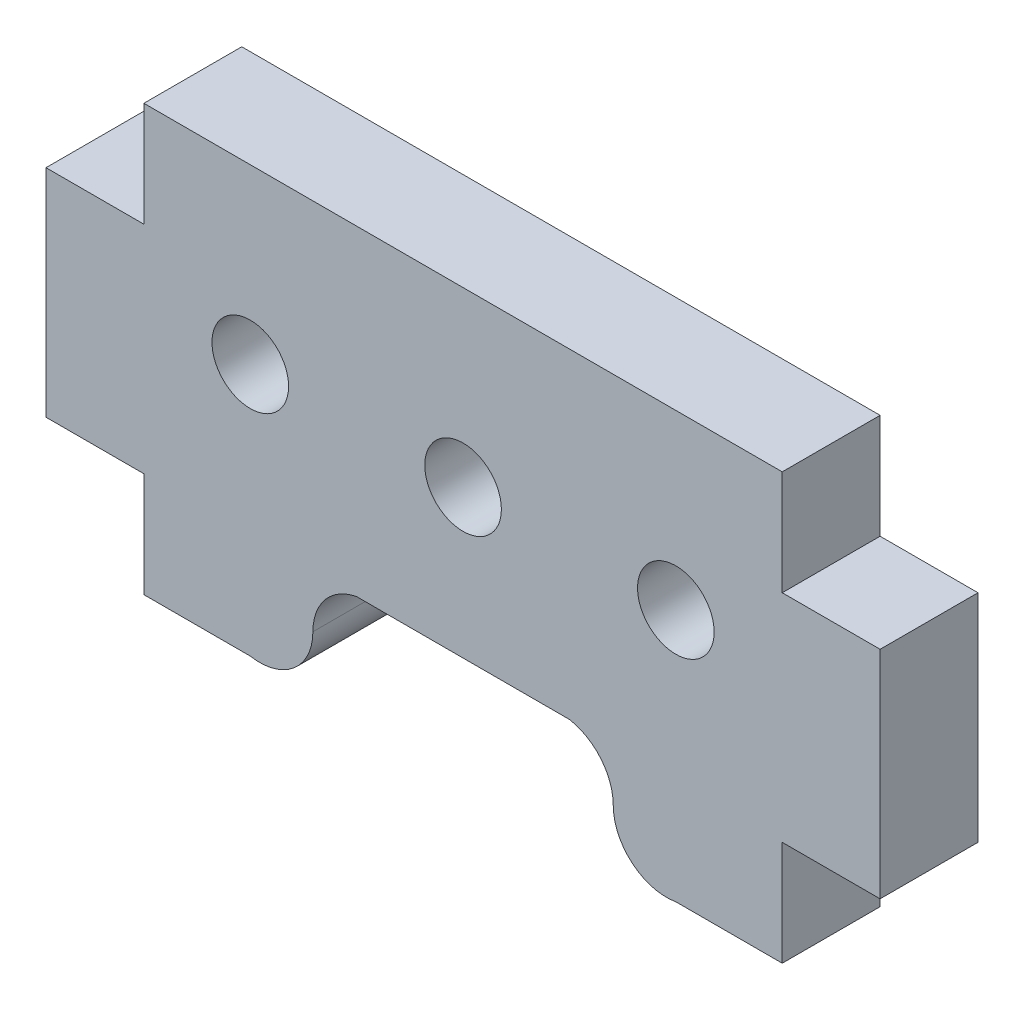
SolidWorks part; units mm, degrees
ref_plane "Front Plane" through (0, 0, 0) normal (0, 0, 1) x (1, 0, 0)
ref_plane "Top Plane" through (0, 0, 0) normal (0, 1, 0) x (1, 0, 0)
ref_plane "Right Plane" through (0, 0, 0) normal (1, 0, 0) x (0, 0, -1)
sketch "Sketch1" plane through (0, 0, 0) normal (0, 0, 1) x (1, 0, 0)
  line L0 (-19.05, 25.4) -> (-19.05, 0) construction
  line L1 (0, 0) -> (-6.35, 0)
  line L2 (0, 0) -> (0, 6.25)
  line L3 (0, 25.4) -> (-38.1, 25.4)
  line L4 (-38.1, 0) -> (-38.1, 6.25)
  line L5 (-38.1, 19.15) -> (-38.1, 25.4)
  line L6 (-38.1, 19.15) -> (-43.942, 19.15)
  line L7 (0, 19.15) -> (5.842, 19.15)
  line L8 (-38.1, 6.25) -> (-43.942, 6.25)
  line L9 (-43.942, 19.15) -> (-43.942, 6.25)
  line L10 (0, 6.25) -> (5.842, 6.25)
  line L11 (5.842, 19.15) -> (5.842, 6.25)
  line L12 (0, 19.15) -> (0, 25.4)
  line L21 (-10.2576, 15.0812) -> (-5.7844, 15.0812) construction
  line L22 (-6.35, 23.2234) -> (-6.35, 12.8447) construction
  line L35 (-12.7, 6.25) -> (-25.4, 6.25)
  line L36 (-38.1, 3.125) -> (0, 3.125) construction
  line L37 (-31.75, 0) -> (-38.1, 0)
  circle A0 centre (-6.35, 15.0812) radius 2.286
  circle A1 centre (-19.05, 15.0812) radius 2.286
  circle A2 centre (-31.75, 15.0812) radius 2.286
  arc A12 (-25.4, 6.25) -> (-28.0138, 3.125) centre (-24.8388, 3.125) ccw
  arc A13 (-31.75, 0) -> (-28.0138, 3.125) centre (-31.1888, 3.125) ccw
  arc A14 (-12.7, 6.25) -> (-10.0862, 3.125) centre (-13.2612, 3.125) cw
  arc A15 (-6.35, 0) -> (-10.0862, 3.125) centre (-6.9112, 3.125) cw
  point P15 (-4.1134, 12.8447)
  point P16 (-8.5866, 17.3178)
  point P17 (-4.1134, 17.3178)
  point P18 (-8.5866, 12.8447)
  point P62 (-19.05, 6.25)
  dimension "D14" = 6.35
  dimension "D15" = 3.175
  dimension "D4" = 4.572
  dimension "D1" = 12.9
  dimension "D2" = 25.4
  dimension "D3" = 38.1
  dimension "D9" = 6.35
  dimension "D10" = 15.0812
  dimension "D11" = 5.842
  dimension "D12" = 6.25
  dimension "D13" = 12.7
extrude "Boss-Extrude1" add sketch "Sketch1" along normal blind 5.842
